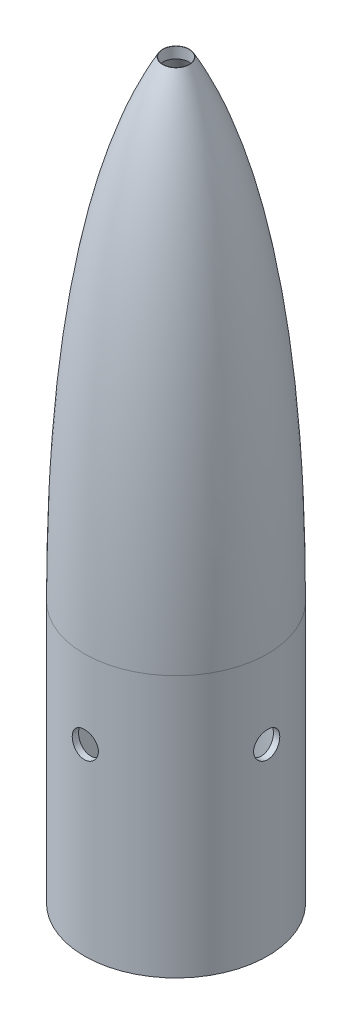
SolidWorks part; units mm, degrees
ref_plane "Piano frontale" through (0, 0, 0) normal (0, 0, 1) x (1, 0, 0)
ref_plane "Piano superiore" through (0, 0, 0) normal (0, 1, 0) x (1, 0, 0)
ref_plane "Piano destro" through (0, 0, 0) normal (1, 0, 0) x (0, 0, -1)
sketch "Schizzo1" plane through (0, 0, 0) normal (0, 1, 0) x (1, 0, 0)
  line L0 (0, -54.0204) -> (0, 55.7677) construction
  line L1 (-109.7881, 0) -> (99.3044, 0) construction
  circle A0 centre (0, 0) radius 17.5
extrude "Estrusione-Estrusione1" add sketch "Schizzo1" along normal blind 50
ref_plane "Piano1" through (0, 140, 0) normal (0, 1, 0) x (1, 0, 0)
sketch "Schizzo7" plane through (0, 0, 0) normal (0, 0, 1) x (1, 0, 0)
  line L3 (19.25, 140) -> (-19.25, 140) construction
  line L4 (0, 140) -> (-2.55, 140)
  line L5 (-17.5, 50) -> (-17.5, 144.4382) construction
  line L6 (-2.55, 140) -> (-17.5, 113.6279) construction
  line L7 (-17.5, 113.6279) -> (-17.5, 50) construction
  line L8 (-28.9012, 113.6279) -> (8.7353, 113.6279) construction
  line L9 (0, 138.8) -> (-2, 138.8)
  line L10 (-2, 138.8) -> (-16.3, 113.6279) construction
  line L11 (-16.3, 113.6279) -> (-16.3, 50) construction
  line L12 (-17.5, 50) -> (-16.3, 50)
  line L13 (0, 138.8) -> (0, 140)
  line L14 (0, 50) -> (0, 140) construction
  line L15 (17.5, 50) -> (-17.5, 50) construction
  spline S0 degree 2 poles (-2.55, 140) (-17.5, 113.6279) (-17.5, 50) knots 0 0 0 1 1 1
  spline S1 degree 2 poles (-2, 138.8) (-16.3, 113.6279) (-16.3, 50) knots 0 0 0 1 1 1
  dimension "D2" = 1.2
  dimension "D1" = 2
  dimension "D3" = 1.2
  dimension "D4" = 2.55
revolve "Rivoluzione1" add sketch "Schizzo7" angle 360 about L14
sketch "Schizzo10" plane through (0, 0, 0) normal (0, 1, 0) x (1, 0, 0)
  circle A0 centre (0, 0) radius 16.3
extrude "Taglio-Estrusione1" cut sketch "Schizzo10" along normal up to next
sketch "Schizzo14" plane through (0, 140, 0) normal (0, 1, 0) x (1, 0, 0)
  circle A0 centre (0, 0) radius 2.5
extrude "Taglio-Estrusione3" cut sketch "Schizzo14" against normal through all and the other way through all
sketch "Sketch1" plane through (0, 0, 0) normal (0, -1, 0) x (1, 0, 0)
  circle A0 centre (0, 0) radius 14.8
  circle M2 centre (0, 0) radius 16.3
extrude "Boss-Extrude3" add sketch "Sketch1" against normal blind 15 contours A0 M2
sketch "Sketch2" plane through (0, 0, 0) normal (0, -1, 0) x (1, 0, 0)
  line L0 (-14.8, 0) -> (14.8, 0)
  line L4 (0, 0) -> (0, 10.7136) construction
  line L8 (-8.3, 4.3829) -> (-14.1361, 4.3829)
  line L9 (-8.3, -4.3829) -> (-14.1361, -4.3829)
  line L10 (8.3, 4.3829) -> (14.1361, 4.3829)
  line L11 (8.3, -4.3829) -> (14.1361, -4.3829)
  circle A0 centre (0, 0) radius 14.8 construction
  arc A1 (-8.3, 4.3829) -> (-8.3, -4.3829) centre (-8.3, 0) cw
  circle A2 centre (-8.3, 0) radius 2.2
  circle A5 centre (0, 0) radius 14.8
  circle A6 centre (8.3, 0) radius 2.2
  arc A7 (8.3, 4.3829) -> (8.3, -4.3829) centre (8.3, 0) ccw
  point P8 (-14.8, 0)
  dimension "D1" = 8.3
extrude "Boss-Extrude4" add sketch "Sketch2" against normal blind 5
ref_plane "Plane1" through (0, 0, 0) normal (0, 0, 1) x (1, 0, 0)
ref_plane "Plane2" through (0, 0, 17.5) normal (0, 0, 1) x (1, 0, 0)
ref_plane "Plane3" through (17.5, 0, 0) normal (1, 0, 0) x (0, 0, -1)
sketch "Sketch4" plane through (0, 0, 17.5) normal (0, 0, 1) x (1, 0, 0)
  line L0 (0, 0) -> (0, 72.0128) construction
  line L1 (0, 72.0128) -> (0, 125.0681) construction
  line L2 (0, 15) -> (0, 0) construction
  line L3 (0, 50) -> (0, 15) construction
  circle A0 centre (0, 35) radius 2.5
  dimension "D1" = 35
extrude "Cut-Extrude1" cut sketch "Sketch4" against normal through all both and the other way through all
sketch "Sketch5" plane through (17.5, 0, 0) normal (1, 0, 0) x (0, 0, -1)
  line L0 (0, 0) -> (0, 75.9251) construction
  circle A0 centre (0, 35) radius 2.5
  dimension "D1" = 35
extrude "Cut-Extrude2" cut sketch "Sketch5" against normal through all both and the other way through all
